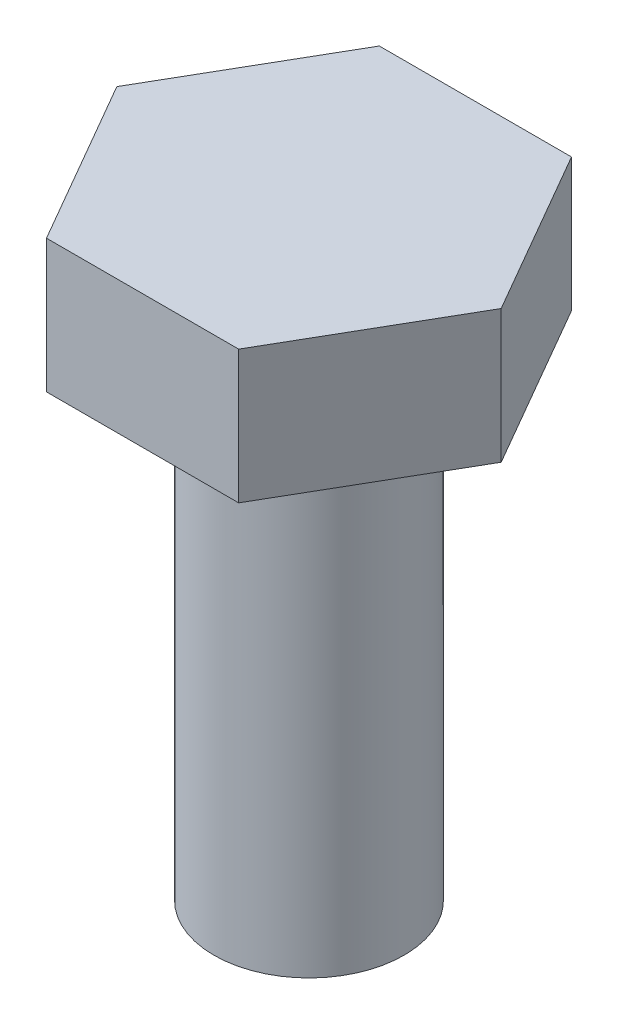
SolidWorks part; units mm, degrees
ref_plane "前视基准面" through (0, 0, 0) normal (0, 0, 1) x (1, 0, 0)
ref_plane "上视基准面" through (0, 0, 0) normal (0, 1, 0) x (1, 0, 0)
ref_plane "右视基准面" through (0, 0, 0) normal (1, 0, 0) x (0, 0, -1)
sketch "草图1" plane through (0, 0, 0) normal (0, 1, 0) x (1, 0, 0)
  circle A0 centre (0, 0) radius 2
  dimension "D1" = 4
extrude "凸台-拉伸1" add sketch "草图1" along normal blind 10
sketch "草图2" plane through (0, 10, 0) normal (0, 1, 0) x (1, 0, 0)
  line L1 (4.0415, 0) -> (2.0207, 3.5)
  line L2 (2.0207, 3.5) -> (-2.0207, 3.5)
  line L3 (-2.0207, 3.5) -> (-4.0415, 0)
  line L4 (-4.0415, 0) -> (-2.0207, -3.5)
  line L5 (-2.0207, -3.5) -> (2.0207, -3.5)
  line L6 (2.0207, -3.5) -> (4.0415, 0)
  circle A0 centre (0, 0) radius 3.5 construction
  dimension "D1" = 7
extrude "凸台-拉伸2" add sketch "草图2" along normal blind 2.8
